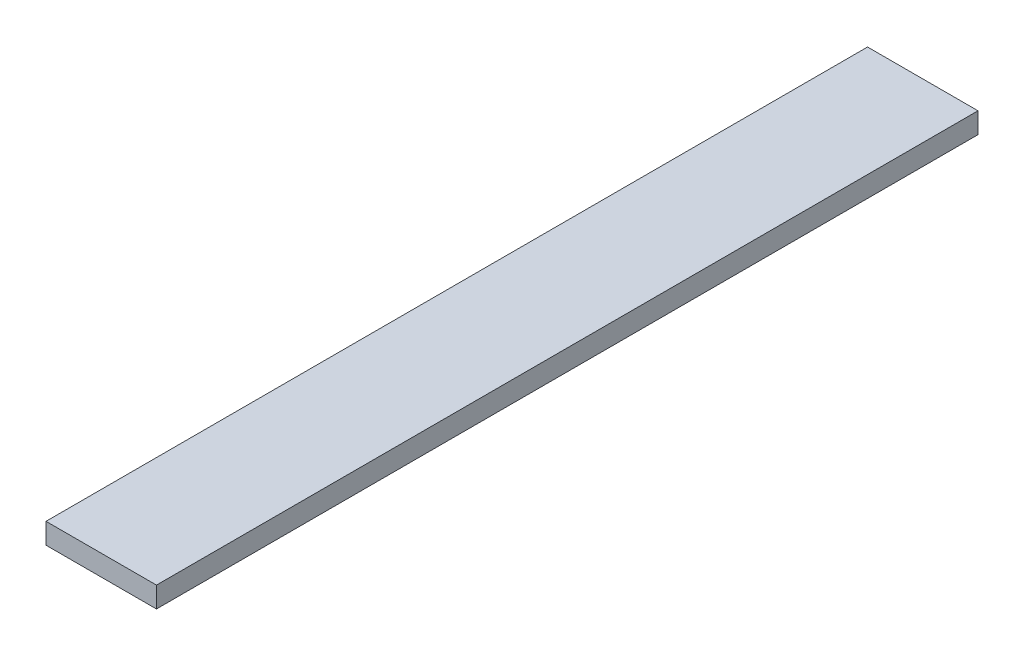
SolidWorks part; units mm, degrees
ref_plane "Front Plane" through (0, 0, 0) normal (0, 0, 1) x (1, 0, 0)
ref_plane "Top Plane" through (0, 0, 0) normal (0, 1, 0) x (1, 0, 0)
ref_plane "Right Plane" through (0, 0, 0) normal (1, 0, 0) x (0, 0, -1)
sketch "Sketch1" plane through (0, 0, 0) normal (0, 1, 0) x (1, 0, 0)
  line L1 (-117.018, -72.5353) -> (-218.618, -72.5353)
  line L2 (-117.018, -72.5353) -> (-117.018, -828.1853)
  line L3 (-117.018, -828.1853) -> (-218.618, -828.1853)
  line L4 (-218.618, -72.5353) -> (-218.618, -828.1853)
  dimension "D1" = 101.6
  dimension "D2" = 755.65
extrude "Boss-Extrude1" add sketch "Sketch1" along normal blind 19.05
